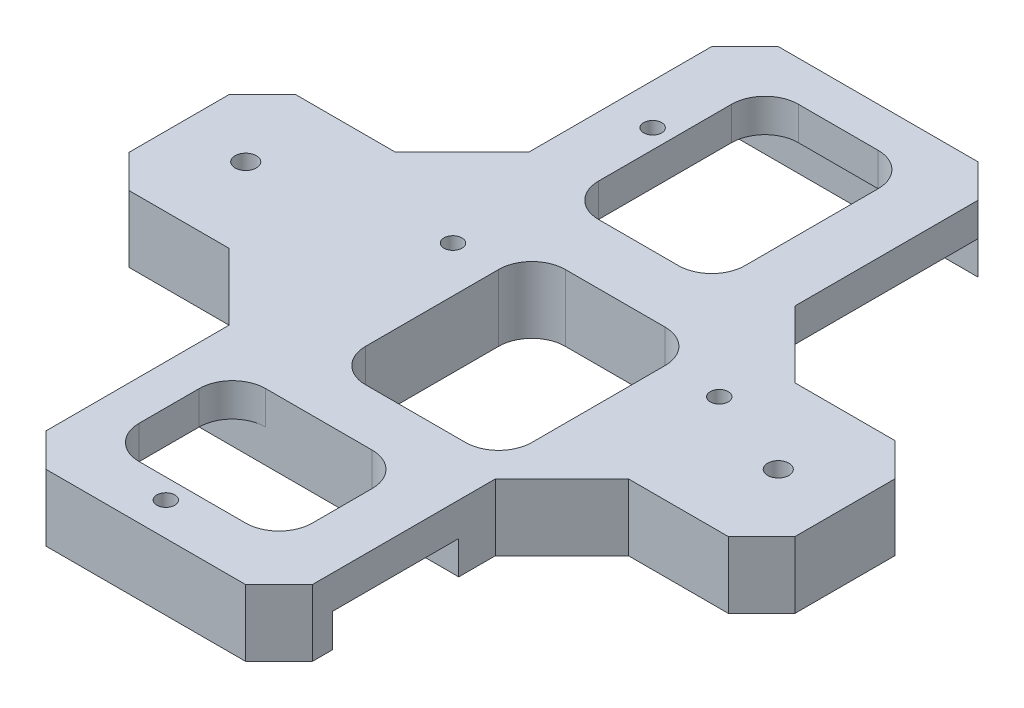
SolidWorks part; units mm, degrees
ref_plane "前视基准面" through (0, 0, 0) normal (0, 0, 1) x (1, 0, 0)
ref_plane "上视基准面" through (0, 0, 0) normal (0, 1, 0) x (1, 0, 0)
ref_plane "右视基准面" through (0, 0, 0) normal (1, 0, 0) x (0, 0, -1)
sketch "草图1" plane through (0, 0, 0) normal (0, 1, 0) x (1, 0, 0)
  line L0 (0, 55) -> (0, -55) construction
  line L1 (-50, 7.5) -> (-50, -7.5)
  line L2 (-40, 0) -> (40, 0) construction
  line L3 (-45, -12.5) -> (-30, -12.5)
  line L4 (-20, -22.5) -> (-20, -50)
  line L5 (-15, -55) -> (15, -55)
  line L6 (20, -50) -> (20, -22.5)
  line L7 (30, -12.5) -> (45, -12.5)
  line L8 (50, -7.5) -> (50, 7.5)
  line L9 (30, 12.5) -> (45, 12.5)
  line L10 (20, 50) -> (20, 22.5)
  line L11 (-15, 55) -> (15, 55)
  line L12 (-20, 22.5) -> (-20, 50)
  line L13 (-45, 12.5) -> (-30, 12.5)
  line L14 (-30, 12.5) -> (-20, 22.5)
  line L15 (-30, -12.5) -> (-20, -22.5)
  line L16 (20, 22.5) -> (30, 12.5)
  line L17 (20, -22.5) -> (30, -12.5)
  line L18 (-50, 7.5) -> (-45, 12.5)
  line L19 (-50, -7.5) -> (-45, -12.5)
  line L20 (-20, -50) -> (-15, -55)
  line L21 (15, -55) -> (20, -50)
  line L22 (45, -12.5) -> (50, -7.5)
  line L23 (45, 12.5) -> (50, 7.5)
  line L24 (15, 55) -> (20, 50)
  line L25 (-20, 50) -> (-15, 55)
  line L27 (-6, 49) -> (6, 49)
  line L28 (-11, 44) -> (-11, 24)
  line L29 (-6, 19) -> (6, 19)
  line L30 (11, 44) -> (11, 24)
  line L31 (-9, -28) -> (7, -28)
  line L32 (-14, -33) -> (-14, -42)
  line L33 (-9, -47) -> (7, -47)
  line L34 (12, -33) -> (12, -42)
  line L35 (-2, 10) -> (13, 10)
  line L36 (-7, 5) -> (-7, -15)
  line L37 (-2, -20) -> (13, -20)
  line L38 (18, 5) -> (18, -15)
  circle A0 centre (40, 0) radius 1.6
  circle A1 centre (-40, 0) radius 1.6
  circle A2 centre (-2, -50) radius 1.35
  circle A3 centre (-13.87, 5) radius 1.35
  circle A4 centre (26.13, 5) radius 1.35
  circle A5 centre (-13.87, 35) radius 1.35
  arc A6 (11, 44) -> (6, 49) centre (6, 44) ccw
  arc A7 (-6, 49) -> (-11, 44) centre (-6, 44) ccw
  arc A8 (-11, 24) -> (-6, 19) centre (-6, 24) ccw
  arc A9 (6, 19) -> (11, 24) centre (6, 24) ccw
  arc A10 (-14, -42) -> (-9, -47) centre (-9, -42) ccw
  arc A11 (7, -47) -> (12, -42) centre (7, -42) ccw
  arc A12 (7, -28) -> (12, -33) centre (7, -33) cw
  arc A13 (-9, -28) -> (-14, -33) centre (-9, -33) ccw
  arc A14 (13, -20) -> (18, -15) centre (13, -15) ccw
  arc A15 (-7, -15) -> (-2, -20) centre (-2, -15) ccw
  arc A16 (-2, 10) -> (-7, 5) centre (-2, 5) ccw
  arc A17 (13, 10) -> (18, 5) centre (13, 5) cw
  point P8 (-50, -12.5)
  point P9 (20, -55)
  point P10 (-20, -12.5)
  point P11 (-20, -55)
  point P12 (20, 12.5)
  point P13 (20, -12.5)
  point P14 (50, -12.5)
  point P17 (50, 12.5)
  point P18 (50, 0)
  point P19 (20, 55)
  point P20 (-20, 55)
  point P21 (-20, 12.5)
  point P22 (-50, 12.5)
  point P23 (-50, 0)
  point P65 (0, 19)
  point P66 (0, 0)
  point P67 (12, -60.5748)
  point P68 (0, 0)
  point P71 (11, 49)
  point P76 (-11, 19)
  point P79 (11, 19)
  point P90 (18, -20)
  point P97 (18, 10)
  dimension "D2" = 3.2
  dimension "D5" = 10
  dimension "D7" = 4
  dimension "D8" = 5
  dimension "D9" = 2.7
  dimension "D10" = 36.13
  dimension "D11" = 5
  dimension "D12" = 40
  dimension "D13" = 30
  dimension "D14" = 2.7
  dimension "D15" = 5
  dimension "D1" = 80
  dimension "D3" = 25
  dimension "D4" = 40
  dimension "D6" = 110
  dimension "D16" = 22
  dimension "D29" = 30
  dimension "D30" = 6
  dimension "D31" = 7
  dimension "D32" = 18
  dimension "D33" = 10
  dimension "D34" = 30
  dimension "D35" = 8
  dimension "D36" = 8
  dimension "D37" = 6
  dimension "D38" = 8
extrude "凸台-拉伸1" add sketch "草图1" along normal blind 10
sketch "草图2" plane through (0, 0, 0) normal (0, -1, 0) x (1, 0, 0)
  circle A0 centre (-40, 0) radius 3
  circle A1 centre (40, 0) radius 3
  dimension "D1" = 6
extrude "切除-拉伸1" cut sketch "草图2" against normal blind 5
sketch "草图3" plane through (0, 0, 0) normal (0, -1, 0) x (1, 0, 0)
  line L0 (-20, 22.5) -> (-20, 50) construction
  line L1 (-20, 47) -> (20, 47)
  line L2 (-20, 47) -> (-20, 28)
  line L3 (-20, 28) -> (20, 28)
  line L4 (20, 47) -> (20, 28)
  line L5 (20, 50) -> (20, 22.5) construction
  line L6 (7, 28) -> (-9, 28) construction
  line L7 (-20, -22.5) -> (20, -22.5)
  line L8 (-20, -22.5) -> (-20, -50)
  line L9 (-20, -50) -> (20, -50)
  line L10 (20, -22.5) -> (20, -50)
  line L11 (-9, 47) -> (7, 47) construction
  point P14 (20, 23.4425)
  point P17 (20, 42.6962)
extrude "切除-拉伸2" cut sketch "草图3" against normal blind 5
